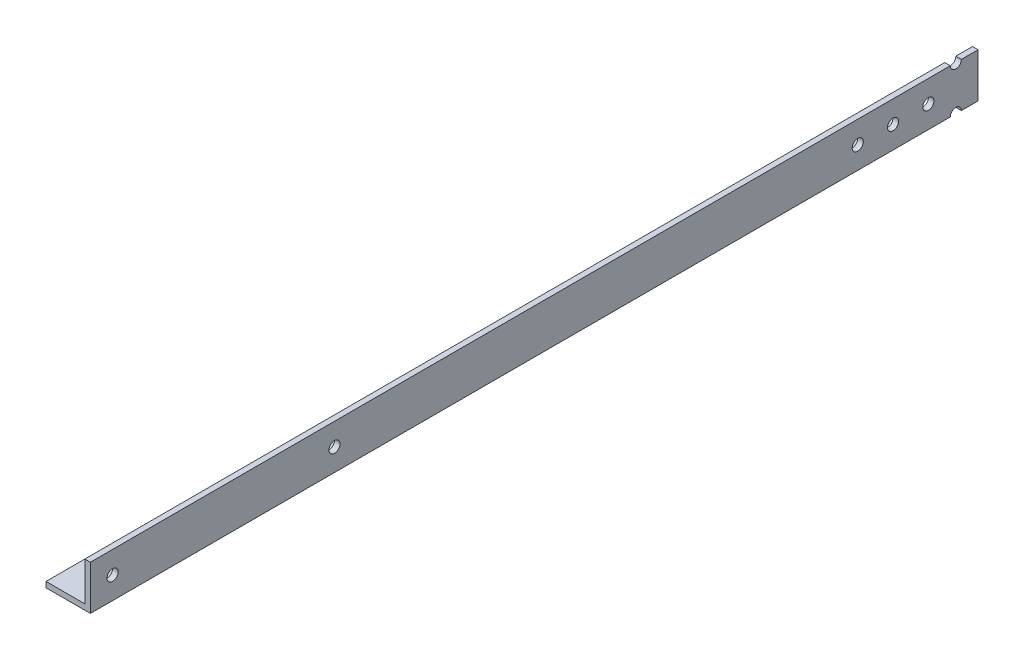
SolidWorks part; units mm, degrees
material "6061 Alloy"
ref_plane "Front Plane" through (0, 0, 0) normal (0, 0, 1) x (1, 0, 0)
ref_plane "Top Plane" through (0, 0, 0) normal (0, 1, 0) x (1, 0, 0)
ref_plane "Right Plane" through (0, 0, 0) normal (1, 0, 0) x (0, 0, -1)
sketch "Sketch1" plane through (0, 0, 0) normal (0, 0, 1) x (1, 0, 0)
  line L0 (0, 0) -> (0, 12.7)
  line L1 (0, 12.7) -> (-1.5875, 12.7)
  line L2 (-1.5875, 12.7) -> (-1.5875, 1.5875)
  line L3 (-1.5875, 1.5875) -> (-12.7, 1.5875)
  line L4 (-12.7, 1.5875) -> (-12.7, 0)
  line L5 (-12.7, 0) -> (0, 0)
  dimension "width" = 12.7
  dimension "thickness" = 1.5875
extrude "Extrude1" add sketch "Sketch1" along normal blind 254
sketch "Sketch2" plane through (0, 0, 0) normal (1, 0, 0) x (0, 0, -1)
  line L0 (-254, 0) -> (0, 0) construction
  line L2 (-254, 0) -> (-254, 12.7) construction
  circle A0 centre (-247.65, 6.35) radius 1.5875
  circle A1 centre (-184.15, 6.35) radius 1.5875
  dimension "D1" = 6.35
  dimension "D2" = 6.35
  dimension "hole_dia" = 3.175
  dimension "D3" = 6.35
  dimension "D4" = 63.5
extrude "Extrude2" cut sketch "Sketch2" against normal up to surface (1.5875 mm away) up to face at (-1.5875, 7.1438, 127)
sketch "Sketch3" plane through (0, 0, 0) normal (1, 0, 0) x (0, 0, -1)
  line L0 (-254, 0) -> (0, 0) construction
  line L1 (0, 0) -> (0, 12.7) construction
  circle A0 centre (-14.2077, 6.35) radius 10.1028
  circle A1 centre (-24.3105, 6.35) radius 1.5875
  circle A2 centre (-6.35, 12.7) radius 1.5875
  circle A3 centre (-6.35, 0) radius 1.5875
  circle A4 centre (-14.2077, 6.35) radius 1.5875
  dimension "D1" = 6.35
  dimension "D2" = 19.05
  dimension "D3" = 19.05
  dimension "D4" = 12.7
  dimension "D5" = 6.35
extrude "Cut-Extrude3" cut sketch "Sketch3" against normal through all contours A4 | A1
sketch "Sketch5" plane through (0, 1.5875, 0) normal (0, 1, 0) x (1, 0, 0)
  line L0 (-1.5875, -254) -> (-1.5875, 0) construction
  line L1 (-12.7, 0) -> (-1.5875, 0)
  line L2 (-12.7, 0) -> (-12.7, -12.7)
  line L3 (-12.7, -12.7) -> (-1.5875, -12.7)
  line L4 (-1.5875, 0) -> (-1.5875, -12.7)
extrude "Cut-Extrude4" cut sketch "Sketch5" against normal up to surface (1.5875 mm away) up to face at (-6.35, 0, 127)
sketch "Sketch6" plane through (0, 0, 0) normal (1, 0, 0) x (0, 0, -1)
  circle A0 centre (-14.2077, 6.35) radius 10.1028
  circle A1 centre (-6.35, 12.7) radius 1.5875
  circle A2 centre (-6.35, 0) radius 1.5875
  circle A3 centre (-24.3105, 6.35) radius 1.5875 construction
  circle A5 centre (-14.2077, 6.35) radius 1.5875 construction
  dimension "D1" = 19.05
  dimension "D2" = 19.05
  dimension "D3" = 6.35
  dimension "D4" = 12.7
extrude "Cut-Extrude5" cut sketch "Sketch6" against normal up to surface (1.5875 mm away) contours A1 | A2 up to face at (-1.5875, 7.9375, 24.3105)
sketch "Sketch7" plane through (0, 0, 0) normal (1, 0, 0) x (0, 0, -1)
  circle A0 centre (-24.3105, 6.35) radius 10.1028
  circle A1 centre (-34.4133, 6.35) radius 1.5875
extrude "Cut-Extrude6" cut sketch "Sketch7" against normal up to surface (1.5875 mm away) contours A1 up to face at (-1.5875, 7.9375, 24.3105)
equation "\"D1@Sketch2\" = \"width\" / 2"
equation "\"D3@Sketch2\" = \"D1@Sketch2\""
equation "\"D1@Sketch3\" = \"width\" / 2"
equation "\"D3@Sketch3\" = \"D2@Sketch3\""
equation "\"D2@Sketch6\" = \"D1@Sketch6\""
